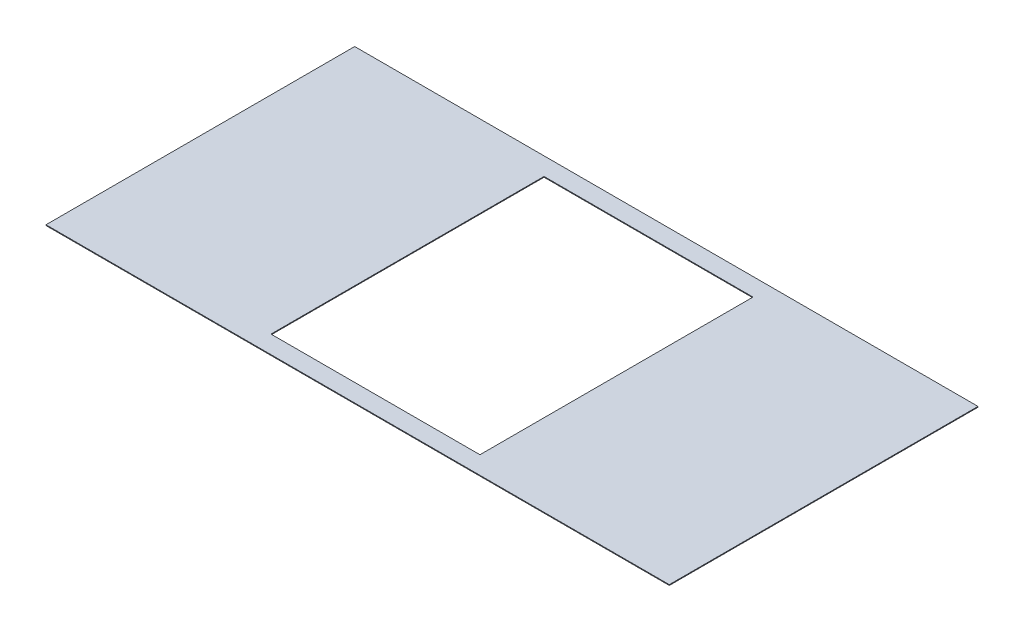
SolidWorks part; units mm, degrees
ref_plane "Alzado" through (0, 0, 0) normal (0, 0, 1) x (1, 0, 0)
ref_plane "Planta" through (0, 0, 0) normal (0, 1, 0) x (1, 0, 0)
ref_plane "Vista lateral" through (0, 0, 0) normal (1, 0, 0) x (0, 0, -1)
sketch "Croquis1" plane through (0, 0, 0) normal (0, 1, 0) x (1, 0, 0)
  line L1 (-525, 260) -> (525, 260)
  line L2 (-525, 260) -> (-525, -260)
  line L3 (-525, -260) -> (525, -260)
  line L4 (525, 260) -> (525, -260)
  line L5 (-525, 260) -> (525, -260) construction
  line L6 (-525, -260) -> (525, 260) construction
  point P0 (0, 0)
  dimension "D1" = 1050
  dimension "D2" = 520
extrude "Saliente-Extruir1" add sketch "Croquis1" along normal blind 1.25
sketch "Croquis2" plane through (0, 1.25, 0) normal (0, 1, 0) x (1, 0, 0)
  line L0 (0, 260) -> (0, -260) construction
  line L1 (525, 260) -> (-525, 260) construction
  line L2 (-525, -260) -> (525, -260) construction
  line L4 (-176, 230) -> (176, 230)
  line L5 (-176, 230) -> (-176, -230)
  line L6 (-176, -230) -> (176, -230)
  line L7 (176, 230) -> (176, -230)
  line L8 (-176, 230) -> (176, -230) construction
  line L9 (-176, -230) -> (176, 230) construction
  point P6 (0, 0)
  dimension "D1" = 30
  dimension "D2" = 352
extrude "Cortar-Extruir1" cut sketch "Croquis2" against normal blind 1.25
